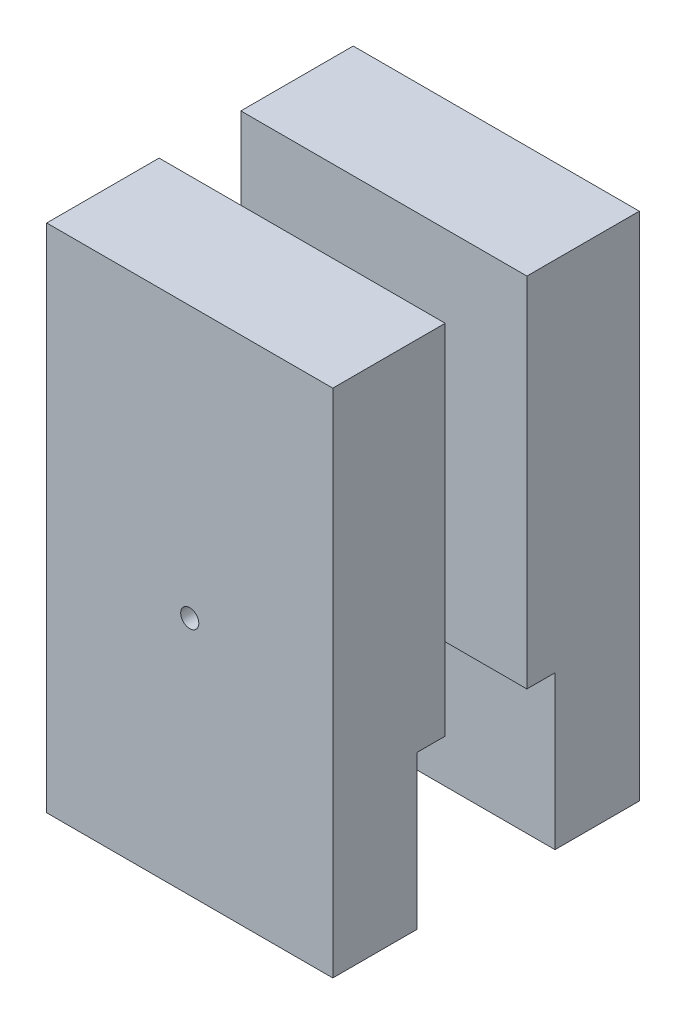
SolidWorks part; units mm, degrees
ref_plane "Front Plane" through (0, 0, 0) normal (0, 0, 1) x (1, 0, 0)
ref_plane "Top Plane" through (0, 0, 0) normal (0, 1, 0) x (1, 0, 0)
ref_plane "Right Plane" through (0, 0, 0) normal (1, 0, 0) x (0, 0, -1)
sketch "Sketch1" plane through (0, 0, 0) normal (0, 1, 0) x (1, 0, 0)
  line L1 (-17.78, 19.05) -> (17.78, 19.05)
  line L2 (-17.78, 19.05) -> (-17.78, -19.05)
  line L3 (-17.78, -19.05) -> (17.78, -19.05)
  line L4 (17.78, 19.05) -> (17.78, -19.05)
  line L5 (-17.78, 19.05) -> (17.78, -19.05) construction
  line L6 (-17.78, -19.05) -> (17.78, 19.05) construction
  point P0 (0, 0)
  dimension "D1" = 38.1
  dimension "D2" = 35.56
extrude "Boss-Extrude1" add sketch "Sketch1" along normal blind 63.5
sketch "Sketch3" plane through (0, 63.5, 0) normal (0, 1, 0) x (1, 0, 0)
  line L0 (17.78, -19.05) -> (17.78, 19.05) construction
  line L1 (-17.78, 5.08) -> (17.78, 5.08)
  line L2 (-17.78, 5.08) -> (-17.78, -5.08)
  line L3 (-17.78, -5.08) -> (17.78, -5.08)
  line L4 (17.78, 5.08) -> (17.78, -5.08)
  line L5 (-17.78, 5.08) -> (17.78, -5.08) construction
  line L6 (-17.78, -5.08) -> (17.78, 5.08) construction
  point P0 (0, 0)
  dimension "D1" = 10.16
extrude "Cut-Extrude1" cut sketch "Sketch3" against normal blind 38.1
sketch "Sketch4" plane through (0, 0, 0) normal (0, -1, 0) x (1, 0, 0)
  line L0 (17.78, 19.05) -> (17.78, -19.05) construction
  line L1 (-17.78, -8.5725) -> (17.78, -8.5725)
  line L2 (-17.78, -8.5725) -> (-17.78, 8.5725)
  line L3 (-17.78, 8.5725) -> (17.78, 8.5725)
  line L4 (17.78, -8.5725) -> (17.78, 8.5725)
  line L5 (-17.78, -8.5725) -> (17.78, 8.5725) construction
  line L6 (-17.78, 8.5725) -> (17.78, -8.5725) construction
  point P0 (0, 0)
  dimension "D1" = 17.145
extrude "Cut-Extrude2" cut sketch "Sketch4" against normal offset from surface (19.05 mm away) 6.35 up to face at (0, 25.4, 0)
sketch "Sketch5" plane through (0, 25.4, 0) normal (0, 1, 0) x (1, 0, 0)
  line L0 (17.78, 5.08) -> (-17.78, 5.08) construction
  line L1 (-0.635, -5.08) -> (0.635, -5.08)
  line L2 (-0.635, -5.08) -> (-0.635, 5.08)
  line L3 (-0.635, 5.08) -> (0.635, 5.08)
  line L4 (0.635, -5.08) -> (0.635, 5.08)
  line L5 (-0.635, -5.08) -> (0.635, 5.08) construction
  line L6 (-0.635, 5.08) -> (0.635, -5.08) construction
  line L7 (-17.78, -8.5725) -> (-17.78, 8.5725) construction
  line L8 (-0.635, 5.08) -> (-17.78, 5.08)
  line L9 (-0.635, 5.08) -> (-0.635, -5.08)
  line L10 (-0.635, -5.08) -> (-17.78, -5.08)
  line L11 (-17.78, 5.08) -> (-17.78, -5.08)
  line L13 (0.635, 5.08) -> (17.78, 5.08)
  line L14 (0.635, 5.08) -> (0.635, -5.08)
  line L15 (0.635, -5.08) -> (17.78, -5.08)
  line L16 (17.78, 5.08) -> (17.78, -5.08)
  point P0 (0, 0)
  line M10 (17.78, -5.08) -> (17.78, 5.08)
  line M11 (17.78, 5.08) -> (-17.78, 5.08)
  line M12 (-17.78, 5.08) -> (-17.78, -5.08)
  line M13 (-17.78, -5.08) -> (17.78, -5.08)
  dimension "D1" = 1.27
extrude "Cut-Extrude3" cut sketch "Sketch5" against normal through all contours L2 M13 M11 M12 | L4 M13 M10 M11
sketch "Sketch6" plane through (0, 0, -5.08) normal (0, 0, 1) x (1, 0, 0)
  line L0 (0.635, 25.4) -> (-0.635, 25.4) construction
  line L1 (0, 0) -> (0, 29.845) construction
  circle A0 centre (0, 29.845) radius 1.125
  dimension "D1" = 2.25
  dimension "D2" = 4.445
extrude "Cut-Extrude4" cut sketch "Sketch6" against normal through all both and the other way through all
